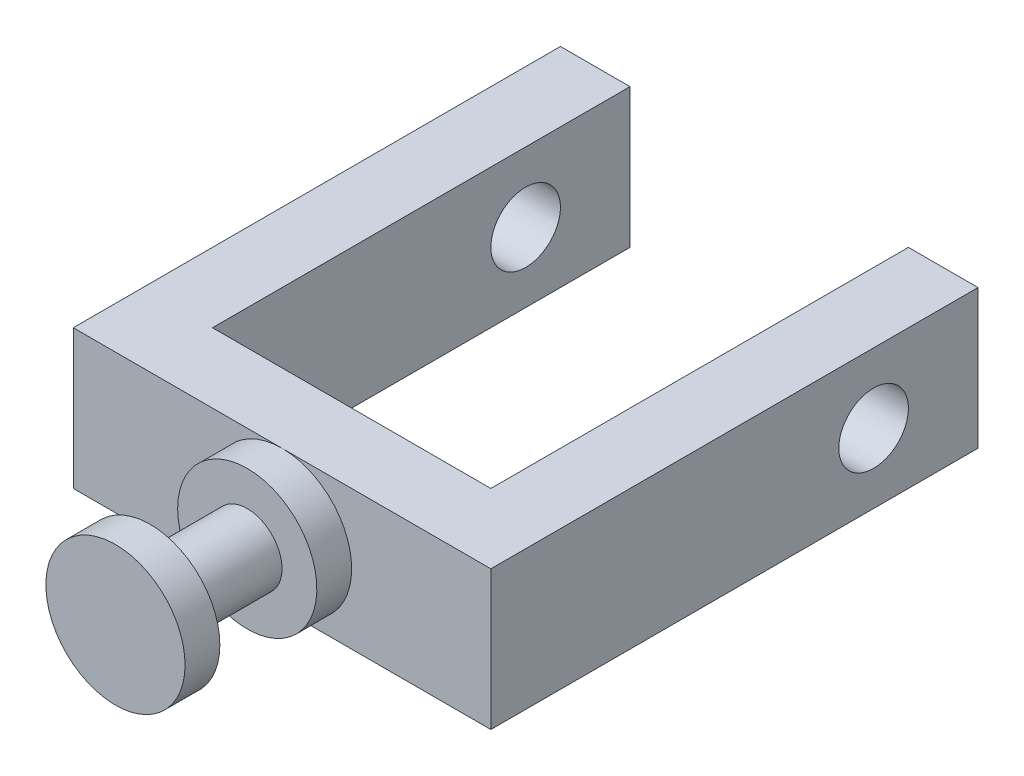
SolidWorks part; units mm, degrees
ref_plane "Front Plane" through (0, 0, 0) normal (0, 0, 1) x (1, 0, 0)
ref_plane "Top Plane" through (0, 0, 0) normal (0, 1, 0) x (1, 0, 0)
ref_plane "Right Plane" through (0, 0, 0) normal (1, 0, 0) x (0, 0, -1)
sketch "Sketch1" plane through (0, 0, 0) normal (0, 0, 1) x (1, 0, 0)
  circle A0 centre (0, 0) radius 25.4
  dimension "D1" = 50.8
extrude "Boss-Extrude1" add sketch "Sketch1" against normal blind 12.7
sketch "Sketch2" plane through (0, 0, -12.7) normal (0, 0, -1) x (-1, 0, 0)
  circle A0 centre (0, 0) radius 12.7
  dimension "D1" = 25.4
extrude "Boss-Extrude2" add sketch "Sketch2" along normal blind 35.4
sketch "Sketch3" plane through (0, 0, -48.1) normal (0, 0, -1) x (-1, 0, 0)
  circle A0 centre (0, 0) radius 25.4
  dimension "D1" = 50.8
extrude "Boss-Extrude3" add sketch "Sketch3" along normal blind 12.7
sketch "Sketch4" plane through (0, 0, -60.8) normal (0, 0, -1) x (-1, 0, 0)
  line L1 (-76.2, 25.4) -> (76.2, 25.4)
  line L2 (-76.2, 25.4) -> (-76.2, -25.4)
  line L3 (-76.2, -25.4) -> (76.2, -25.4)
  line L4 (76.2, 25.4) -> (76.2, -25.4)
  line L5 (-76.2, 25.4) -> (76.2, -25.4) construction
  line L6 (-76.2, -25.4) -> (76.2, 25.4) construction
  point P0 (0, 0)
  dimension "D1" = 152.4
  dimension "D2" = 50.8
extrude "Boss-Extrude4" add sketch "Sketch4" along normal blind 25.4 contours L1 L4 L3 L2
sketch "Sketch5" plane through (0, 0, -86.2) normal (0, 0, -1) x (-1, 0, 0)
  line L0 (0, 0.897) -> (0, 30.4971) construction
  line L1 (-50.8, -25.4) -> (-76.2, -25.4)
  line L2 (-50.8, -25.4) -> (-50.8, 25.4)
  line L3 (-50.8, 25.4) -> (-76.2, 25.4)
  line L4 (-76.2, -25.4) -> (-76.2, 25.4)
  line L5 (-50.8, -25.4) -> (-76.2, 25.4) construction
  line L6 (-50.8, 25.4) -> (-76.2, -25.4) construction
  line L7 (50.8, 25.4) -> (76.2, -25.4) construction
  line L8 (50.8, -25.4) -> (76.2, 25.4) construction
  line L9 (76.2, -25.4) -> (76.2, 25.4)
  line L10 (50.8, 25.4) -> (76.2, 25.4)
  line L11 (50.8, -25.4) -> (50.8, 25.4)
  line L12 (50.8, -25.4) -> (76.2, -25.4)
  point P0 (-63.5, 0)
  point P13 (63.5, 0)
  dimension "D1" = 25.4
  dimension "D2" = 50.8
extrude "Boss-Extrude5" add sketch "Sketch5" along normal blind 152.4
sketch "Sketch6" plane through (-76.2, 0, 0) normal (-1, 0, 0) x (0, 0, 1)
  circle A0 centre (-200.5, 0) radius 12.7
  dimension "D2" = 25.4
  dimension "D1" = 139.7
extrude "Cut-Extrude1" cut sketch "Sketch6" against normal through all both and the other way through all
